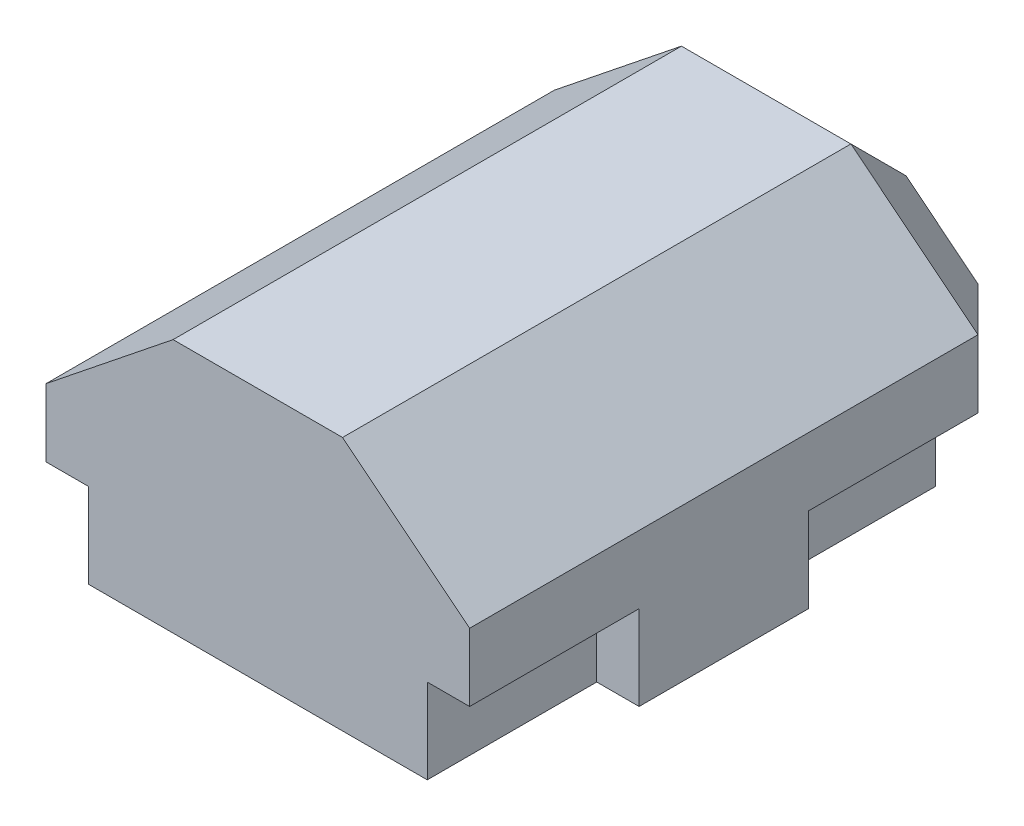
SolidWorks part; units mm, degrees
ref_plane "Plan de face" through (0, 0, 0) normal (0, 0, 1) x (1, 0, 0)
ref_plane "Plan de dessus" through (0, 0, 0) normal (0, 1, 0) x (1, 0, 0)
ref_plane "Plan de droite" through (0, 0, 0) normal (1, 0, 0) x (0, 0, -1)
sketch "Esquisse1" plane through (0, 0, 0) normal (0, 0, 1) x (1, 0, 0)
  line L0 (-250, 30) -> (-100, 150)
  line L1 (200, -150) -> (-200, -150)
  line L2 (250, -50) -> (250, 30)
  line L3 (100, 150) -> (-100, 150)
  line L4 (-250, -50) -> (-250, 30)
  line L5 (200, -120) -> (-164.2857, 98.5714) construction
  line L6 (164.2857, 98.5714) -> (-200, -120) construction
  line L7 (0, 150) -> (0, -150) construction
  line L8 (-250, -50) -> (-200, -50)
  line L9 (-200, -50) -> (-200, -150)
  line L10 (200, -50) -> (200, -150)
  line L11 (250, -50) -> (200, -50)
  line L12 (250, 30) -> (100, 150)
  point P0 (0, 0)
  dimension "D1" = 300
  dimension "D3" = 30
  dimension "D4" = 100
  dimension "D5" = 50
  dimension "D6" = 100
extrude "Boss.-Extru.1" add sketch "Esquisse1" along normal blind 600
sketch "Esquisse2" plane through (-250, 0, 0) normal (-1, 0, 0) x (0, 0, 1)
  line L0 (200, -50) -> (200, -150)
  line L1 (600, -50) -> (0, -50) construction
  line L2 (600, -150) -> (0, -150) construction
  line L3 (200, -150) -> (400, -150)
  line L4 (400, -150) -> (400, -50)
  line L5 (600, -50) -> (0, -50) construction
  line L6 (400, -50) -> (200, -50)
  line L7 (0, -50) -> (0, -150) construction
  line L8 (600, -50) -> (600, -150) construction
  dimension "D1" = 200
  dimension "D2" = 200
extrude "Boss.-Extru.2" add sketch "Esquisse2" against normal blind 500
sketch "Esquisse3" plane through (0, 0, 0) normal (0, 0, -1) x (-1, 0, 0)
  line L0 (-200, -50) -> (200, -50)
  line L10 (250, -50) -> (250, 30)
  line L11 (250, 30) -> (100, 150)
  line L12 (100, 150) -> (-100, 150)
  line L13 (-100, 150) -> (-250, 30)
  line L14 (-250, 30) -> (-250, -50)
  line L15 (-250, -50) -> (-200, -50)
  line L16 (-200, -50) -> (-200, -150)
  line L17 (-200, -150) -> (200, -150)
  line L18 (200, -150) -> (200, -50)
  line L19 (200, -50) -> (250, -50)
  line L20 (250, -50) -> (250, 30)
  line L21 (250, 30) -> (100, 150)
  line L22 (100, 150) -> (-100, 150)
  line L23 (-100, 150) -> (-250, 30)
  line L24 (-250, 30) -> (-250, -50)
  line L25 (-250, -50) -> (-200, -50)
  line L29 (200, -50) -> (250, -50)
  dimension "D1" = 0
extrude "Boss.-Extru.3" add sketch "Esquisse3" along normal blind 100
chamfer "Chanfrein1" distance 100 angle 45 5 edges at (-250, -10, -100) (-175, 90, -100) (0, 150, -100) (250, -10, -100) (175, 90, -100)
